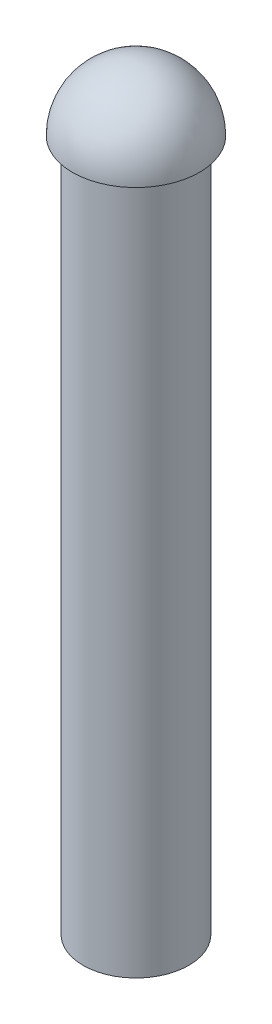
SolidWorks part; units mm, degrees
ref_plane "前视基准面" through (0, 0, 0) normal (0, 0, 1) x (1, 0, 0)
ref_plane "上视基准面" through (0, 0, 0) normal (0, 1, 0) x (1, 0, 0)
ref_plane "右视基准面" through (0, 0, 0) normal (1, 0, 0) x (0, 0, -1)
other "Configuration Table"
sketch "草图1" plane through (0, 0, 0) normal (0, 1, 0) x (1, 0, 0)
  line L0 (0, 7.8) -> (0, -7.8)
  arc A0 (0, -7.8) -> (0, 7.8) centre (0, 0) ccw
  dimension "D1" = 15.6
revolve "旋转1" add sketch "草图1" angle 180 about L0
sketch "草图6" plane through (0, 0, 0) normal (1, 0, 0) x (0, 0, -1)
  line L1 (0, 0) -> (6.5, 0)
  line L2 (0, 0) -> (0, -85)
  line L3 (0, -85) -> (6.5, -85)
  line L4 (6.5, 0) -> (6.5, -85)
  dimension "D1" = 6.5
  dimension "D2" = 85
revolve "旋转2" add sketch "草图6" angle 360 about L2
